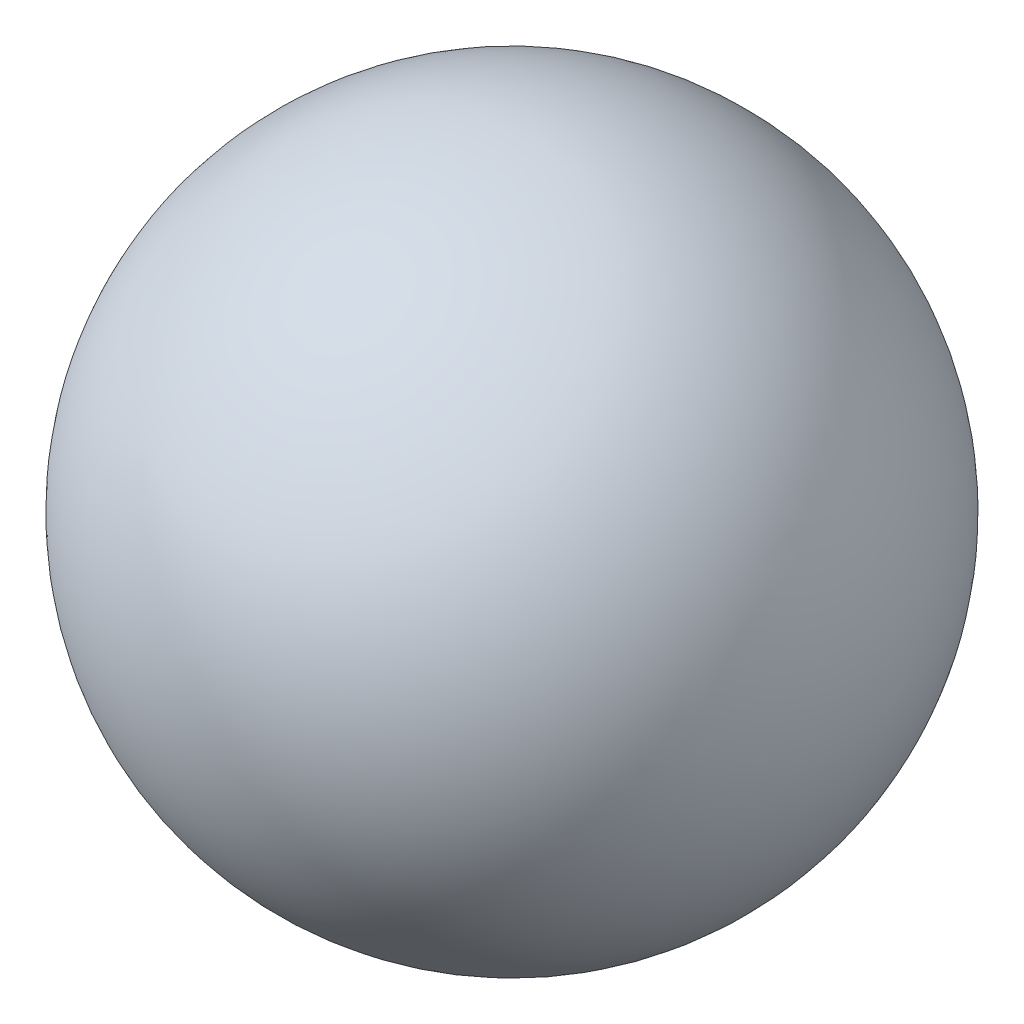
SolidWorks part; units mm, degrees
ref_plane "Front Plane" through (0, 0, 0) normal (0, 0, 1) x (1, 0, 0)
ref_plane "Top Plane" through (0, 0, 0) normal (0, 1, 0) x (1, 0, 0)
ref_plane "Right Plane" through (0, 0, 0) normal (1, 0, 0) x (0, 0, -1)
sketch "Sketch1" plane through (0, 0, 0) normal (0, 0, 1) x (1, 0, 0)
  line L0 (-12, 0) -> (12, 0)
  arc A0 (12, 0) -> (-12, 0) centre (0, 0) cw
  dimension "D1" = 24
revolve "Revolve1" add sketch "Sketch1" angle 360 about L0
scale "Scale1" scale about centroid uniform scaling yes scale factor 0.35
